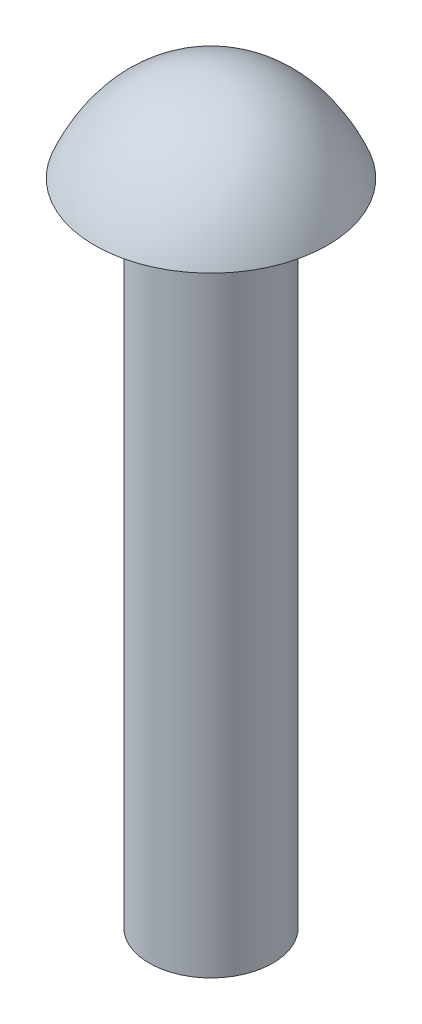
SolidWorks part; units mm, degrees
ref_plane "Front Plane" through (0, 0, 0) normal (0, 0, 1) x (1, 0, 0)
ref_plane "Top Plane" through (0, 0, 0) normal (0, 1, 0) x (1, 0, 0)
ref_plane "Right Plane" through (0, 0, 0) normal (1, 0, 0) x (0, 0, -1)
sketch "Sketch3" plane through (0, 0, 0) normal (0, 0, 1) x (1, 0, 0)
  line L0 (-18.2937, 0) -> (-15.8807, 0)
  line L1 (-15.8807, 0) -> (-15.8807, 25.4)
  line L2 (-15.8807, 25.4) -> (-13.7344, 25.4)
  line L3 (-18.2937, 0) -> (-18.2937, 28.8798)
  line L4 (-19.3956, 28.8798) -> (-17.1917, 28.8798) construction
  spline S0 degree 3 poles (-13.7344, 25.4) (-13.9583, 25.9467) (-15.1773, 28.8798) (-18.2937, 28.8798) knots 0 0 0 0 1 1 1 1
  point P6 (-15.8807, 27.8943)
  point P7 (-19.638, 24.4318)
  point P9 (0, 0)
  point P12 (0, 0)
  point P13 (-15.3661, 27.8212)
  point P14 (-15.1955, 27.6201)
  dimension "D1" = 3.4798
  dimension "D2" = 25.4
  dimension "D3" = 2.413
  dimension "D4" = 4.5593
revolve "Revolve1" add sketch "Sketch3" angle 360 about L3
